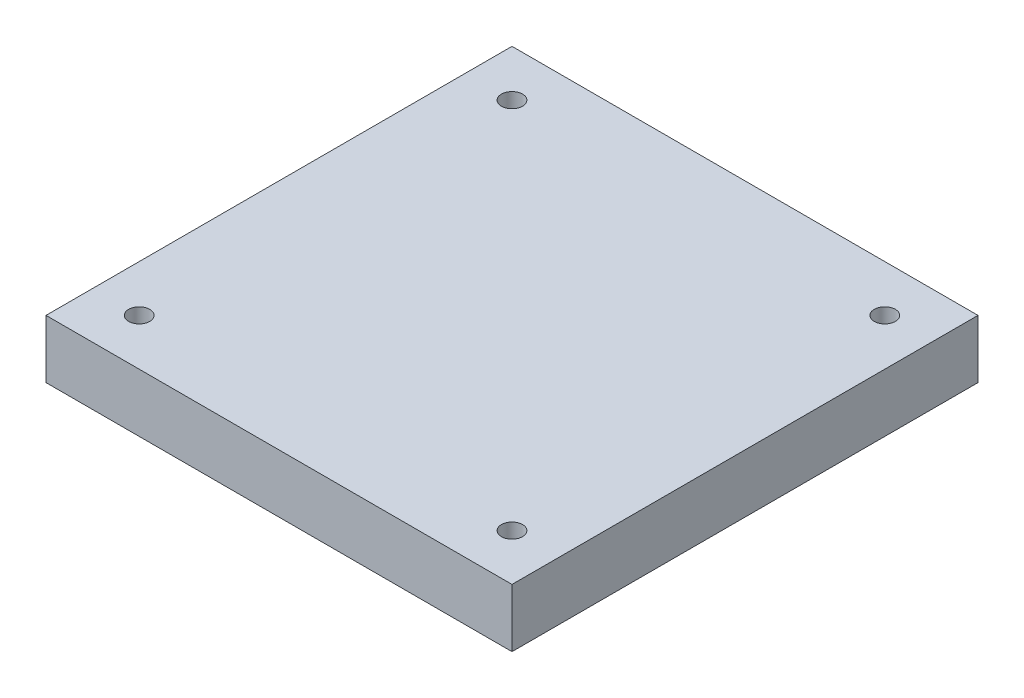
SolidWorks part; units mm, degrees
ref_plane "Front Plane" through (0, 0, 0) normal (0, 0, 1) x (1, 0, 0)
ref_plane "Top Plane" through (0, 0, 0) normal (0, 1, 0) x (1, 0, 0)
ref_plane "Right Plane" through (0, 0, 0) normal (1, 0, 0) x (0, 0, -1)
sketch "Sketch1" plane through (0, 0, 0) normal (0, 0, 1) x (1, 0, 0)
  line L7 (-50.8, -6.35) -> (50.8, -6.35)
  line L8 (-50.8, -6.35) -> (-50.8, 6.35)
  line L9 (-50.8, 6.35) -> (50.8, 6.35)
  line L10 (50.8, -6.35) -> (50.8, 6.35)
  line L11 (-50.8, -6.35) -> (50.8, 6.35) construction
  line L12 (-50.8, 6.35) -> (50.8, -6.35) construction
  point P4 (0, 0)
  point P14 (0, 0)
  dimension "Width" = 101.6
  dimension "Thickness" = 12.7
sketch "Sketch2" plane through (0, 0, 0) normal (0, 1, 0) x (0, 0, -1)
  line L0 (50.8, 50.8) -> (-50.8, 50.8) construction
  point P0 (76.2, 50.8)
  point P4 (0, 50.8)
  point P6 (-76.2, 50.8)
  dimension "Length" = 101.6
  dimension "D1" = 127
  dimension "D2" = 127
sketch "Sketch3" plane through (0, 0, 0) normal (0, 0, 1) x (1, 0, 0)
  line L6 (-50.8, 6.35) -> (50.8, 6.35)
  line L7 (50.8, 6.35) -> (50.8, -6.35)
  line L8 (50.8, -6.35) -> (-50.8, -6.35)
  line L9 (-50.8, -6.35) -> (-50.8, 6.35)
extrude "Boss-Extrude1" add sketch "Sketch3" along normal mid plane 101.6
ref_plane "FacingTop" through (0, 5.9531, 0) normal (0, 1, 0) x (1, 0, 0)
other "FacingTopSurfaceCut"
ref_plane "FacingBottom" through (0, -5.9531, 0) normal (0, -1, 0) x (-1, 0, 0)
other "FacingBottomSurfaceCut"
sketch "BaseBorderRadiusSketch" plane through (0, 5.9531, 0) normal (0, 1, 0) x (1, 0, 0)
  line L0 (50.8, -50.8) -> (50.8, 50.8) construction
  line L1 (-47.625, -47.625) -> (47.625, -47.625)
  line L2 (-47.625, -47.625) -> (-47.625, 47.625)
  line L3 (-47.625, 47.625) -> (47.625, 47.625)
  line L4 (47.625, -47.625) -> (47.625, 47.625)
  line L5 (-47.625, -47.625) -> (47.625, 47.625) construction
  line L6 (-47.625, 47.625) -> (47.625, -47.625) construction
  point P0 (0, 0)
  dimension "D1" = 3.175
extrude "BaseBorderRadiusCut-Extrude" cut sketch "BaseBorderRadiusSketch" against normal through all flip side to cut
sketch "BumperInsetSketch" plane through (0, -5.9531, 0) normal (0, -1, 0) x (1, 0, 0)
  line L1 (-38.1, -38.1) -> (38.1, -38.1) construction
  line L2 (-38.1, -38.1) -> (-38.1, 38.1) construction
  line L3 (-38.1, 38.1) -> (38.1, 38.1) construction
  line L4 (38.1, -38.1) -> (38.1, 38.1) construction
  line L5 (-38.1, -38.1) -> (38.1, 38.1) construction
  line L6 (-38.1, 38.1) -> (38.1, -38.1) construction
  line L7 (47.625, 47.625) -> (47.625, -47.625) construction
  circle A0 centre (-38.1, 38.1) radius 5.715
  circle A1 centre (38.1, 38.1) radius 5.715
  circle A2 centre (38.1, -38.1) radius 5.715
  circle A3 centre (-38.1, -38.1) radius 5.715
  point P0 (0, 0)
  dimension "D2" = 11.43
  dimension "D1" = 9.525
hole_wizard "Bumper#6-32 Tapped Hole" positions "3DSketch4" profile "Sketch11" counterbore size "#6" standard "ANSI Inch" end condition through all
sketch3d "3DSketch4"
  point P0 (-38.1, -5.9531, 38.1)
sketch "Sketch11" plane through (-38.1, -5.9531, 38.1) normal (1, 0, 0) x (0, 0, -1)
  line L0 (0, 0) -> (0, 11.9062)
  line L1 (0, 11.9062) -> (2.1526, 11.9062)
  line L3 (2.1526, 11.9062) -> (2.1526, 5.3848)
  line L4 (2.1526, 5.3848) -> (3.9688, 5.3848)
  line L5 (3.9688, 5.3848) -> (3.9688, 0)
  line L7 (3.9688, 0) -> (0, 0)
  line L11 (0, -6.35) -> (0, 107.95) construction
  dimension "Thru Hole Dia." = 4.3053
  dimension "Thru Hole Depth" = 11.9062
  dimension "C'Bore Dia." = 7.9375
  dimension "C'Bore Depth" = 5.3848
pattern_linear "BumperThreadLPattern" count 2 spacing 76.2 along (0, 0, -1) count 2 spacing 76.2 along (1, 0, 0) of "Bumper#6-32 Tapped Hole"
equation "\"D1@Boss-Extrude1\" = \"Length@Sketch2\""
equation "\"D1@Sketch2\"=\"Width@Sketch1\" * 1.25"
equation "\"D2@Sketch2\"=\"D1@Sketch2\""
